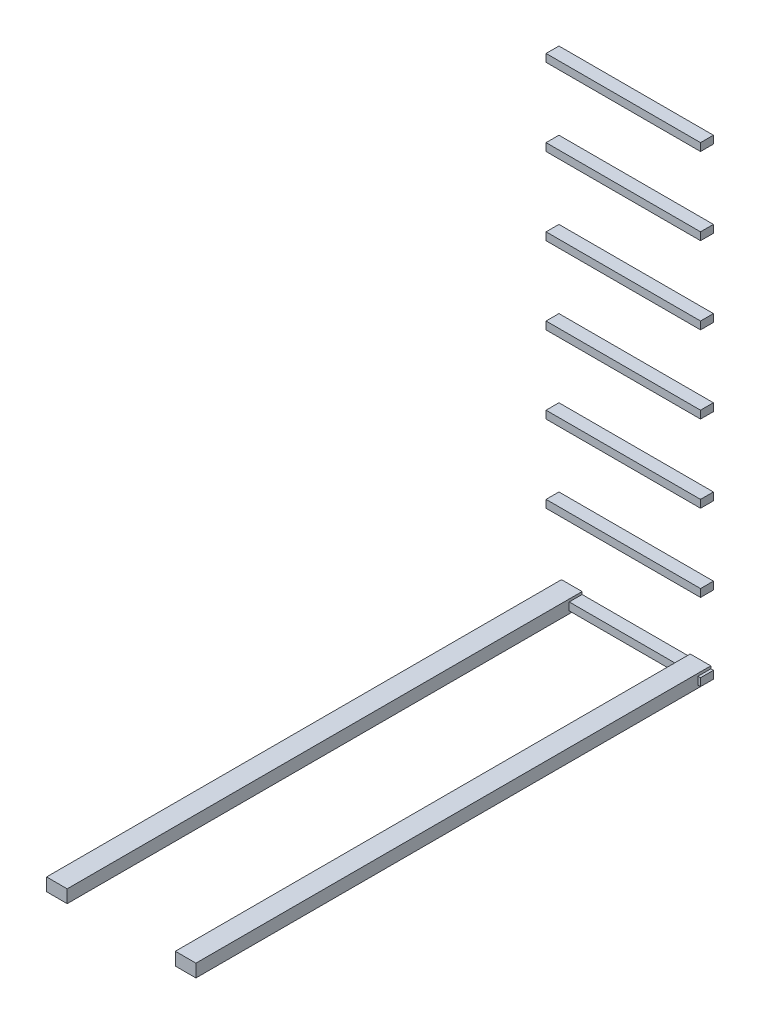
SolidWorks part; units mm, degrees
ref_plane "前视基准面" through (0, 0, 0) normal (0, 0, 1) x (1, 0, 0)
ref_plane "上视基准面" through (0, 0, 0) normal (0, 1, 0) x (1, 0, 0)
ref_plane "右视基准面" through (0, 0, 0) normal (1, 0, 0) x (0, 0, -1)
other "Configuration Table"
sketch "草图1" plane through (0, 0, 0) normal (0, 0, 1) x (1, 0, 0)
  line L1 (-290, -25) -> (-210, -25)
  line L2 (-290, -25) -> (-290, 25)
  line L3 (-290, 25) -> (-210, 25)
  line L4 (-210, -25) -> (-210, 25)
  line L5 (-290, -25) -> (-210, 25) construction
  line L6 (-290, 25) -> (-210, -25) construction
  point P0 (-250, 0)
extrude "凸台-拉伸1" add sketch "草图1" along normal blind 2000
sketch "草图2" plane through (0, 0, 0) normal (0, 0, 1) x (1, 0, 0)
  line L1 (210, -25) -> (290, -25)
  line L2 (210, -25) -> (210, 25)
  line L3 (210, 25) -> (290, 25)
  line L4 (290, -25) -> (290, 25)
  line L5 (210, -25) -> (290, 25) construction
  line L6 (210, 25) -> (290, -25) construction
  point P0 (250, 0)
extrude "凸台-拉伸2" add sketch "草图2" along normal blind 2000
sketch "草图3" plane through (0, 0, 0) normal (0, 0, 1) x (1, 0, 0)
  line L1 (-300, -15) -> (300, -15)
  line L2 (-300, -15) -> (-300, 15)
  line L3 (-300, 15) -> (300, 15)
  line L4 (300, -15) -> (300, 15)
  line L5 (-300, -15) -> (300, 15) construction
  line L6 (-300, 15) -> (300, -15) construction
  point P0 (0, 0)
extrude "凸台-拉伸3" add sketch "草图3" along normal blind 50
sketch "草图4" plane through (0, 0, 0) normal (0, 0, 1) x (1, 0, 0)
  line L1 (-300, 285) -> (300, 285)
  line L2 (-300, 285) -> (-300, 315)
  line L3 (-300, 315) -> (300, 315)
  line L4 (300, 285) -> (300, 315)
  line L5 (-300, 285) -> (300, 315) construction
  line L6 (-300, 315) -> (300, 285) construction
  point P0 (0, 300)
extrude "凸台-拉伸4" add sketch "草图4" along normal blind 50
sketch "草图5" plane through (0, 0, 0) normal (0, 0, 1) x (1, 0, 0)
  line L1 (-300, 585) -> (300, 585)
  line L2 (-300, 585) -> (-300, 615)
  line L3 (-300, 615) -> (300, 615)
  line L4 (300, 585) -> (300, 615)
  line L5 (-300, 585) -> (300, 615) construction
  line L6 (-300, 615) -> (300, 585) construction
  point P0 (0, 600)
extrude "凸台-拉伸5" add sketch "草图5" along normal blind 50
sketch "草图6" plane through (0, 0, 0) normal (0, 0, 1) x (1, 0, 0)
  line L1 (-300, 885) -> (300, 885)
  line L2 (-300, 885) -> (-300, 915)
  line L3 (-300, 915) -> (300, 915)
  line L4 (300, 885) -> (300, 915)
  line L5 (-300, 885) -> (300, 915) construction
  line L6 (-300, 915) -> (300, 885) construction
  point P0 (0, 900)
extrude "凸台-拉伸6" add sketch "草图6" along normal blind 50
sketch "草图7" plane through (0, 0, 0) normal (0, 0, 1) x (1, 0, 0)
  line L1 (-300, 1185) -> (300, 1185)
  line L2 (-300, 1185) -> (-300, 1215)
  line L3 (-300, 1215) -> (300, 1215)
  line L4 (300, 1185) -> (300, 1215)
  line L5 (-300, 1185) -> (300, 1215) construction
  line L6 (-300, 1215) -> (300, 1185) construction
  point P0 (0, 1200)
extrude "凸台-拉伸7" add sketch "草图7" along normal blind 50
sketch "草图8" plane through (0, 0, 0) normal (0, 0, 1) x (1, 0, 0)
  line L1 (-300, 1485) -> (300, 1485)
  line L2 (-300, 1485) -> (-300, 1515)
  line L3 (-300, 1515) -> (300, 1515)
  line L4 (300, 1485) -> (300, 1515)
  line L5 (-300, 1485) -> (300, 1515) construction
  line L6 (-300, 1515) -> (300, 1485) construction
  point P0 (0, 1500)
extrude "凸台-拉伸8" add sketch "草图8" along normal blind 50
sketch "草图9" plane through (0, 0, 0) normal (0, 0, 1) x (1, 0, 0)
  line L1 (-300, 1785) -> (300, 1785)
  line L2 (-300, 1785) -> (-300, 1815)
  line L3 (-300, 1815) -> (300, 1815)
  line L4 (300, 1785) -> (300, 1815)
  line L5 (-300, 1785) -> (300, 1815) construction
  line L6 (-300, 1815) -> (300, 1785) construction
  point P0 (0, 1800)
extrude "凸台-拉伸9" add sketch "草图9" along normal blind 50
